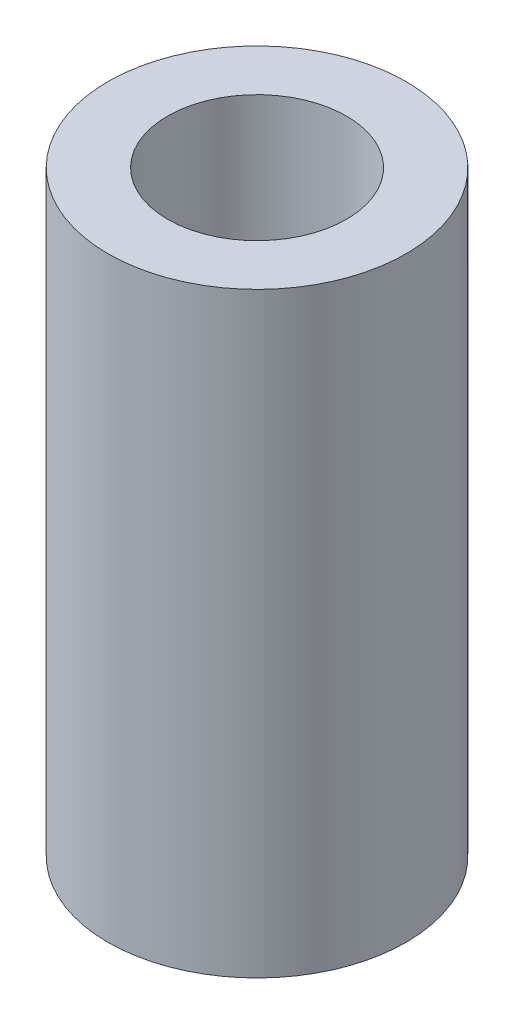
SolidWorks part; units mm, degrees
ref_plane "Front Plane" through (0, 0, 0) normal (0, 0, 1) x (1, 0, 0)
ref_plane "Top Plane" through (0, 0, 0) normal (0, 1, 0) x (1, 0, 0)
ref_plane "Right Plane" through (0, 0, 0) normal (1, 0, 0) x (0, 0, -1)
sketch "Sketch1" plane through (0, 0, 0) normal (0, 1, 0) x (1, 0, 0)
  circle A0 centre (0, 0) radius 3
  circle A1 centre (0, 0) radius 5
  dimension "D1" = 6
  dimension "D2" = 10
extrude "Boss-Extrude1" add sketch "Sketch1" along normal blind 20
